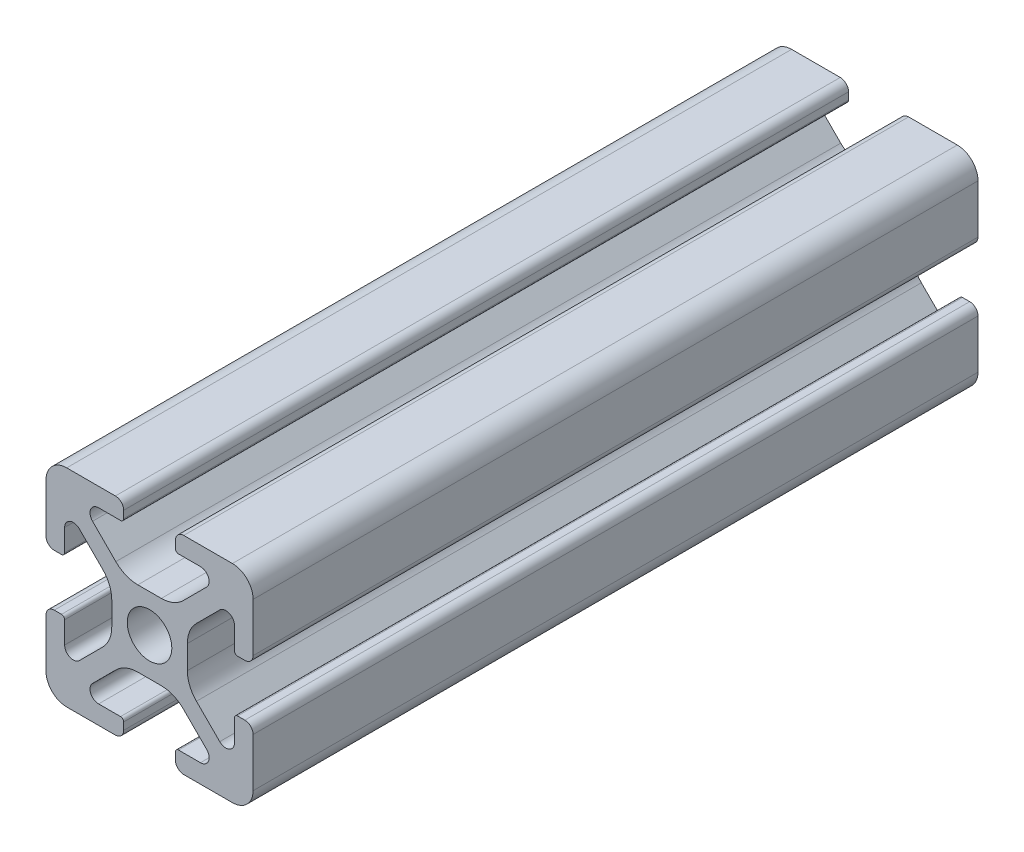
SolidWorks part; units mm, degrees
material "3.0205 (EN-AW 1200)"
ref_plane "Plan de face" through (0, 0, 0) normal (0, 0, 1) x (1, 0, 0)
ref_plane "Plan de dessus" through (0, 0, 0) normal (0, 1, 0) x (1, 0, 0)
ref_plane "Plan de droite" through (0, 0, 0) normal (1, 0, 0) x (0, 0, -1)
ref_plane "Plan1" through (0, 0, 0) normal (0, 0, -1) x (-1, 0, 0)
sketch "Esquisse1" plane through (0, 0, 0) normal (0, 0, -1) x (-1, 0, 0)
  line L0 (-12.5, 0.8) -> (-12.5, 1.5)
  line L1 (-12.8, 1.8) -> (-14.9176, 1.8)
  line L2 (-15.5062, 3.221) -> (-13.2559, 5.4713)
  line L3 (-11.1346, 6.35) -> (-8.8654, 6.35)
  line L4 (-6.7441, 5.4713) -> (-4.4938, 3.221)
  line L5 (-5.0824, 1.8) -> (-7.2, 1.8)
  line L6 (-7.5, 1.5) -> (-7.5, 0.8)
  line L7 (-6.7, 0) -> (-2, 0)
  line L8 (0, 2) -> (0, 6.7)
  line L9 (-0.8, 7.5) -> (-1.5, 7.5)
  line L10 (-1.8, 7.2) -> (-1.8, 5.0824)
  line L11 (-3.221, 4.4938) -> (-5.4713, 6.7441)
  line L12 (-6.35, 8.8654) -> (-6.35, 11.1346)
  line L13 (-5.4713, 13.2559) -> (-3.221, 15.5062)
  line L14 (-1.8, 14.9176) -> (-1.8, 12.8)
  line L15 (-1.5, 12.5) -> (-0.8, 12.5)
  line L16 (0, 13.3) -> (0, 18)
  line L17 (-2, 20) -> (-6.7, 20)
  line L18 (-7.5, 19.2) -> (-7.5, 18.5)
  line L19 (-7.2, 18.2) -> (-5.0824, 18.2)
  line L20 (-4.4938, 16.779) -> (-6.7441, 14.5287)
  line L21 (-8.8654, 13.65) -> (-11.1346, 13.65)
  line L22 (-13.2559, 14.5287) -> (-15.5062, 16.779)
  line L23 (-14.9176, 18.2) -> (-12.8, 18.2)
  line L24 (-12.5, 18.5) -> (-12.5, 19.2)
  line L25 (-13.3, 20) -> (-18, 20)
  line L26 (-20, 18) -> (-20, 13.3)
  line L27 (-19.2, 12.5) -> (-18.5, 12.5)
  line L28 (-18.2, 12.8) -> (-18.2, 14.9176)
  line L29 (-16.779, 15.5062) -> (-14.5287, 13.2559)
  line L30 (-13.65, 11.1346) -> (-13.65, 8.8654)
  line L31 (-14.5287, 6.7441) -> (-16.779, 4.4938)
  line L32 (-18.2, 5.0824) -> (-18.2, 7.2)
  line L33 (-18.5, 7.5) -> (-19.2, 7.5)
  line L34 (-20, 6.7) -> (-20, 2)
  line L35 (-18, 0) -> (-13.3, 0)
  arc A0 (-12.5, 1.5) -> (-12.8, 1.8) centre (-12.8, 1.5) ccw
  arc A1 (-14.9176, 1.8) -> (-15.5062, 3.221) centre (-14.9176, 2.6324) cw
  arc A2 (-13.2559, 5.4713) -> (-11.1346, 6.35) centre (-11.1346, 3.35) cw
  arc A3 (-8.8654, 6.35) -> (-6.7441, 5.4713) centre (-8.8654, 3.35) cw
  arc A4 (-4.4938, 3.221) -> (-5.0824, 1.8) centre (-5.0824, 2.6324) cw
  arc A5 (-7.2, 1.8) -> (-7.5, 1.5) centre (-7.2, 1.5) ccw
  arc A6 (-7.5, 0.8) -> (-6.7, 0) centre (-6.7, 0.8) ccw
  arc A7 (-2, 0) -> (0, 2) centre (-2, 2) ccw
  arc A8 (0, 6.7) -> (-0.8, 7.5) centre (-0.8, 6.7) ccw
  arc A9 (-1.5, 7.5) -> (-1.8, 7.2) centre (-1.5, 7.2) ccw
  arc A10 (-1.8, 5.0824) -> (-3.221, 4.4938) centre (-2.6324, 5.0824) cw
  arc A11 (-5.4713, 6.7441) -> (-6.35, 8.8654) centre (-3.35, 8.8654) cw
  arc A12 (-6.35, 11.1346) -> (-5.4713, 13.2559) centre (-3.35, 11.1346) cw
  arc A13 (-3.221, 15.5062) -> (-1.8, 14.9176) centre (-2.6324, 14.9176) cw
  arc A14 (-1.8, 12.8) -> (-1.5, 12.5) centre (-1.5, 12.8) ccw
  arc A15 (-0.8, 12.5) -> (0, 13.3) centre (-0.8, 13.3) ccw
  arc A16 (0, 18) -> (-2, 20) centre (-2, 18) ccw
  arc A17 (-6.7, 20) -> (-7.5, 19.2) centre (-6.7, 19.2) ccw
  arc A18 (-7.5, 18.5) -> (-7.2, 18.2) centre (-7.2, 18.5) ccw
  arc A19 (-5.0824, 18.2) -> (-4.4938, 16.779) centre (-5.0824, 17.3676) cw
  arc A20 (-6.7441, 14.5287) -> (-8.8654, 13.65) centre (-8.8654, 16.65) cw
  arc A21 (-11.1346, 13.65) -> (-13.2559, 14.5287) centre (-11.1346, 16.65) cw
  arc A22 (-15.5062, 16.779) -> (-14.9176, 18.2) centre (-14.9176, 17.3676) cw
  arc A23 (-12.8, 18.2) -> (-12.5, 18.5) centre (-12.8, 18.5) ccw
  arc A24 (-12.5, 19.2) -> (-13.3, 20) centre (-13.3, 19.2) ccw
  arc A25 (-18, 20) -> (-20, 18) centre (-18, 18) ccw
  arc A26 (-20, 13.3) -> (-19.2, 12.5) centre (-19.2, 13.3) ccw
  arc A27 (-18.5, 12.5) -> (-18.2, 12.8) centre (-18.5, 12.8) ccw
  arc A28 (-18.2, 14.9176) -> (-16.779, 15.5062) centre (-17.3676, 14.9176) cw
  arc A29 (-14.5287, 13.2559) -> (-13.65, 11.1346) centre (-16.65, 11.1346) cw
  arc A30 (-13.65, 8.8654) -> (-14.5287, 6.7441) centre (-16.65, 8.8654) cw
  arc A31 (-16.779, 4.4938) -> (-18.2, 5.0824) centre (-17.3676, 5.0824) cw
  arc A32 (-18.2, 7.2) -> (-18.5, 7.5) centre (-18.5, 7.2) ccw
  arc A33 (-19.2, 7.5) -> (-20, 6.7) centre (-19.2, 6.7) ccw
  arc A34 (-20, 2) -> (-18, 0) centre (-18, 2) ccw
  arc A35 (-13.3, 0) -> (-12.5, 0.8) centre (-13.3, 0.8) ccw
  circle A36 centre (-10, 10) radius 2.15
extrude "Boss.-Extru.1" add sketch "Esquisse1" against normal mid plane 70
